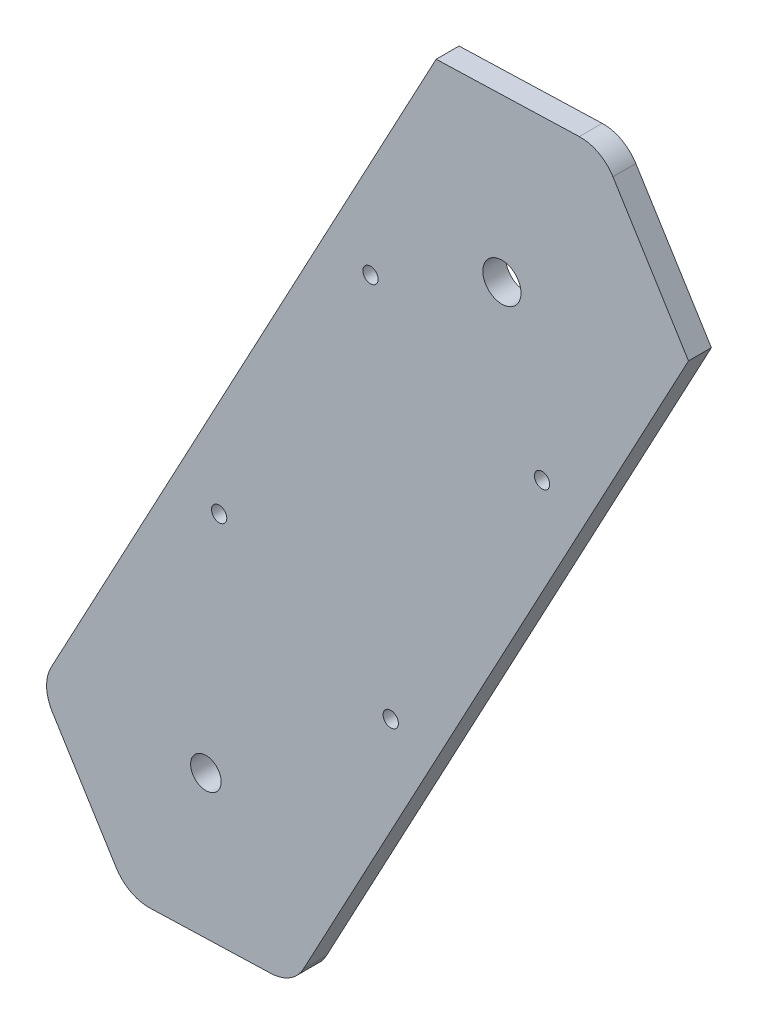
SolidWorks part; units mm, degrees
ref_plane "Front Plane" through (0, 0, 0) normal (0, 0, 1) x (1, 0, 0)
ref_plane "Top Plane" through (0, 0, 0) normal (0, 1, 0) x (1, 0, 0)
ref_plane "Right Plane" through (0, 0, 0) normal (1, 0, 0) x (0, 0, -1)
sketch "Sketch1" plane through (0, 0, 0) normal (0, 0, 1) x (1, 0, 0)
  line L6 (-91.1337, 81.8567) -> (-59.3957, 82.8728)
  line L7 (-116.6985, 113.5548) -> (-99.9495, 86.577)
  line L8 (-50.8998, 88.1473) -> (49.9945, 276.5806)
  line L9 (49.9945, 276.5806) -> (30.2002, 308.4636)
  line L10 (21.3844, 313.1839) -> (-16.1241, 311.983)
  line L11 (-16.1241, 311.983) -> (-117.0184, 123.5497)
  circle A10 centre (11.6281, 230.3485) radius 2
  circle A11 centre (1.1048, 270.0128) radius 5
  circle A12 centre (-33.3325, 254.4221) radius 2
  circle A13 centre (-28.0225, 156.2957) radius 2
  circle A14 centre (-72.9832, 180.3693) radius 2
  circle A15 centre (-76.4646, 119.8455) radius 4
  arc A16 (-99.9495, 86.577) -> (-91.1337, 81.8567) centre (-91.4537, 91.8515) ccw
  arc A17 (-117.0184, 123.5497) -> (-116.6985, 113.5548) centre (-108.2026, 118.8294) ccw
  arc A18 (-59.3957, 82.8728) -> (-50.8998, 88.1473) centre (-59.7157, 92.8676) ccw
  arc A19 (30.2002, 308.4636) -> (21.3844, 313.1839) centre (21.7044, 303.189) ccw
  point P1 (0, 0)
  point P3 (0, 0)
  point P5 (-96.174, 83.0357)
  point P7 (0, 0)
  point P30 (-75.7277, 107.9358)
  point P32 (-73.0496, 113.9007)
  dimension "D3" = 10
  dimension "D11" = 8
  dimension "D12" = 4
  dimension "D13" = 4
  dimension "D14" = 4
  dimension "D15" = 4
  dimension "D28" = 10
  dimension "D1" = 213.7446
  dimension "D2" = 37.5278
  dimension "D4" = 31.7543
  dimension "D5" = 120
  dimension "D6" = 60
  dimension "D7" = 120
  dimension "D8" = 60
  dimension "D9" = 60
  dimension "D10" = 60
  dimension "D16" = 84
  dimension "D17" = 51
  dimension "D18" = 84
  dimension "D19" = 51
  dimension "D20" = 12
  dimension "D21" = 12
  dimension "D22" = 88.1473
  dimension "D23" = 50.8998
  dimension "D24" = 84.7309
  dimension "D25" = 41.7543
  dimension "D26" = 37.5
  dimension "D27" = 169.0185
  dimension "D29" = 40
  dimension "D30" = 41.0366
  dimension "D31" = 12
extrude "Boss-Extrude1" add sketch "Sketch1" along normal blind 6 separate body
